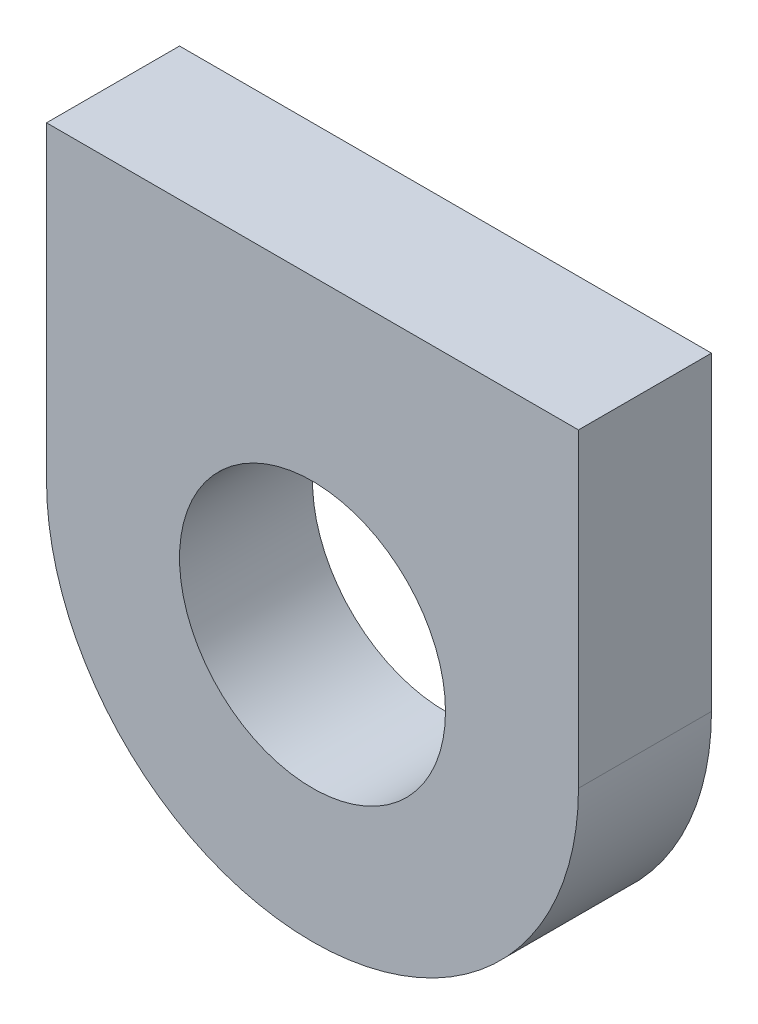
SolidWorks part; units mm, degrees
ref_plane "Front Plane" through (0, 0, 0) normal (0, 0, 1) x (1, 0, 0)
ref_plane "Top Plane" through (0, 0, 0) normal (0, 1, 0) x (1, 0, 0)
ref_plane "Right Plane" through (0, 0, 0) normal (1, 0, 0) x (0, 0, -1)
sketch "Sketch1" plane through (0, 0, 0) normal (0, 0, 1) x (1, 0, 0)
  line L0 (-30, 0) -> (-30, 35)
  line L1 (-30, 35) -> (30, 35)
  line L2 (30, 35) -> (30, 0)
  circle A0 centre (0, 0) radius 15
  arc A1 (-30, 0) -> (30, 0) centre (0, 0) ccw
  circle A3 centre (0, 0) radius 30 construction
  point P8 (30, 0)
  dimension "D1" = 30
  dimension "D3" = 35
  dimension "D2" = 15
extrude "Boss-Extrude1" add sketch "Sketch1" along normal blind 15
